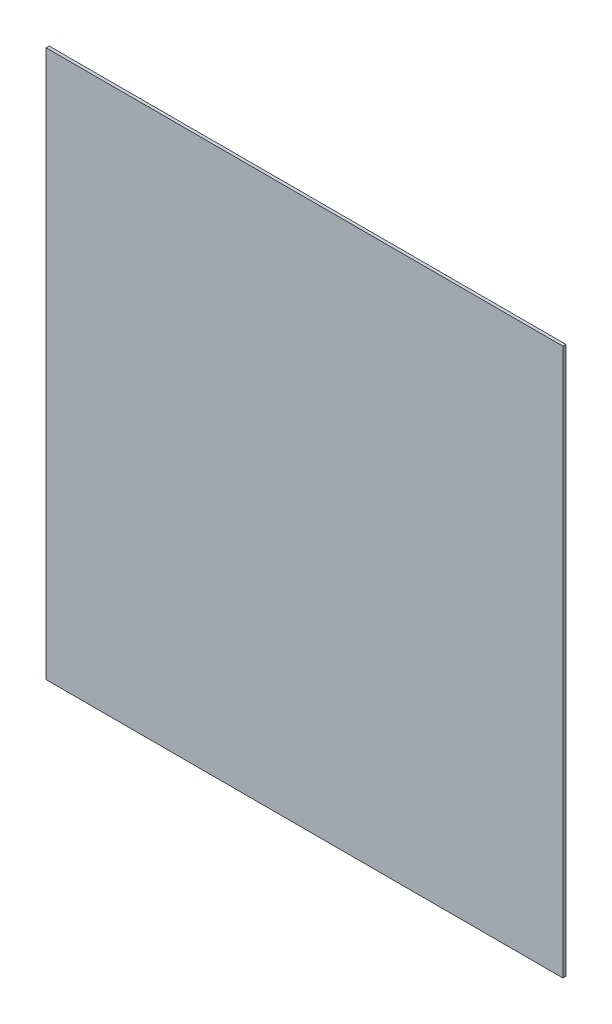
SolidWorks part; units mm, degrees
ref_plane "Front Plane" through (0, 0, 0) normal (0, 0, 1) x (1, 0, 0)
ref_plane "Top Plane" through (0, 0, 0) normal (0, 1, 0) x (1, 0, 0)
ref_plane "Right Plane" through (0, 0, 0) normal (1, 0, 0) x (0, 0, -1)
sketch "Sketch1" plane through (0, 0, 0) normal (0, 0, 1) x (1, 0, 0)
  line L1 (255, 270) -> (-255, 270)
  line L2 (255, 270) -> (255, -270)
  line L3 (255, -270) -> (-255, -270)
  line L4 (-255, 270) -> (-255, -270)
  line L5 (255, 270) -> (-255, -270) construction
  line L6 (255, -270) -> (-255, 270) construction
  point P0 (0, 0)
  dimension "D1" = 540
  dimension "D2" = 510
extrude "Boss-Extrude1" add sketch "Sketch1" along normal blind 3
